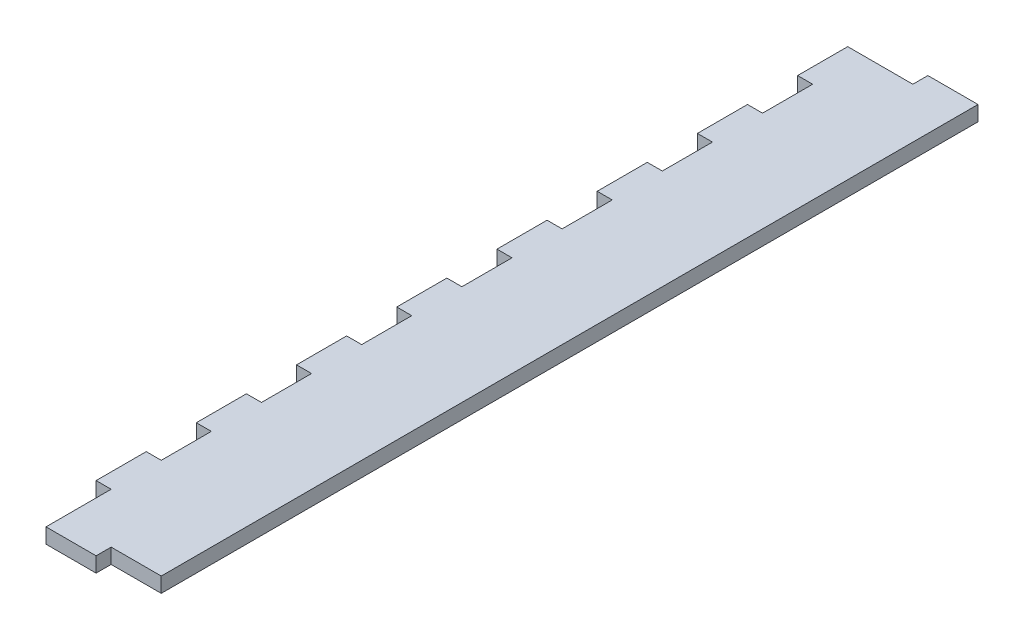
SolidWorks part; units mm, degrees
ref_plane "Front Plane" through (0, 0, 0) normal (0, 0, 1) x (1, 0, 0)
ref_plane "Top Plane" through (0, 0, 0) normal (0, 1, 0) x (1, 0, 0)
ref_plane "Right Plane" through (0, 0, 0) normal (1, 0, 0) x (0, 0, -1)
sketch "Sketch1" plane through (0, 0, 0) normal (0, 1, 0) x (1, 0, 0)
  line L0 (40, 80) -> (40, 70)
  line L1 (43, 70) -> (43, 60)
  line L2 (43, 60) -> (40, 60)
  line L3 (40, 70) -> (43, 70)
  line L4 (40, 60) -> (40, 50)
  line L5 (40, 50) -> (43, 50)
  line L6 (43, 50) -> (43, 40)
  line L7 (43, 40) -> (40, 40)
  line L8 (40, 40) -> (40, 30)
  line L9 (40, 30) -> (43, 30)
  line L10 (43, 30) -> (43, 20)
  line L11 (43, 20) -> (40, 20)
  line L12 (40, 20) -> (40, 10)
  line L13 (40, 10) -> (43, 10)
  line L14 (43, 10) -> (43, 0)
  line L15 (43, 0) -> (40, 0)
  line L16 (40, 0) -> (40, -10)
  line L17 (40, -10) -> (43, -10)
  line L18 (43, -10) -> (43, -20)
  line L19 (43, -20) -> (40, -20)
  line L20 (40, -20) -> (40, -30)
  line L21 (40, -30) -> (43, -30)
  line L22 (43, -30) -> (43, -40)
  line L23 (43, -40) -> (40, -40)
  line L24 (40, -40) -> (40, -50)
  line L25 (40, -50) -> (43, -50)
  line L26 (43, -50) -> (43, -60)
  line L27 (43, -60) -> (40, -60)
  line L28 (40, -60) -> (40, -70)
  line L29 (40, -70) -> (43, -70)
  line L30 (43, -70) -> (43, -80)
  line L31 (43, -80) -> (40, -80)
  line L32 (40, 80) -> (40, -80) construction
  line L33 (-956.5342, 0) -> (49043.4658, 0) construction
  line L34 (-40, -80) -> (-40, -70)
  line L35 (-43, -70) -> (-43, -60)
  line L36 (-43, -60) -> (-40, -60)
  line L37 (-40, -70) -> (-43, -70)
  line L38 (-40, -60) -> (-40, -50)
  line L39 (-40, -50) -> (-43, -50)
  line L40 (-43, -50) -> (-43, -40)
  line L41 (-43, -40) -> (-40, -40)
  line L42 (-40, -40) -> (-40, -30)
  line L43 (-40, -30) -> (-43, -30)
  line L44 (-43, -30) -> (-43, -20)
  line L45 (-43, -20) -> (-40, -20)
  line L46 (-40, -20) -> (-40, -10)
  line L47 (-40, -10) -> (-43, -10)
  line L48 (-43, -10) -> (-43, 0)
  line L49 (-43, 0) -> (-40, 0)
  line L50 (-40, 0) -> (-40, 10)
  line L51 (-40, 10) -> (-43, 10)
  line L52 (-43, 10) -> (-43, 20)
  line L53 (-43, 20) -> (-40, 20)
  line L54 (-40, 20) -> (-40, 30)
  line L55 (-40, 30) -> (-43, 30)
  line L56 (-43, 30) -> (-43, 40)
  line L57 (-43, 40) -> (-40, 40)
  line L58 (-40, 40) -> (-40, 50)
  line L59 (-40, 50) -> (-43, 50)
  line L60 (-43, 50) -> (-43, 60)
  line L61 (-43, 60) -> (-40, 60)
  line L62 (-40, 60) -> (-40, 70)
  line L63 (-40, 70) -> (-43, 70)
  line L64 (-43, 70) -> (-43, 80)
  line L65 (-43, 80) -> (-40, 80)
  line L66 (-40, -80) -> (-40, 80) construction
  line L67 (-40, 80) -> (-30, 80)
  line L68 (-30, 83) -> (-20, 83)
  line L69 (-20, 83) -> (-20, 80)
  line L70 (-30, 80) -> (-30, 83)
  line L71 (-20, 80) -> (-10, 80)
  line L72 (-40, 80) -> (40, 80) construction
  line L73 (-10, 80) -> (-10, 83)
  line L74 (-10, 83) -> (0, 83)
  line L75 (0, 83) -> (0, 80)
  line L76 (0, 80) -> (10, 80)
  line L77 (10, 80) -> (10, 83)
  line L78 (10, 83) -> (20, 83)
  line L79 (20, 83) -> (20, 80)
  line L80 (20, 80) -> (30, 80)
  line L81 (30, 80) -> (30, 83)
  line L82 (30, 83) -> (40, 83)
  line L83 (40, 83) -> (40, 80)
  line L84 (30, -83) -> (20, -83)
  line L85 (20, -83) -> (20, -80)
  line L86 (30, -80) -> (30, -83)
  line L87 (20, -80) -> (10, -80)
  line L88 (10, -80) -> (10, -83)
  line L89 (10, -83) -> (0, -83)
  line L90 (0, -83) -> (0, -80)
  line L91 (0, -80) -> (-10, -80)
  line L92 (-10, -80) -> (-10, -83)
  line L93 (-10, -83) -> (-20, -83)
  line L94 (-20, -83) -> (-20, -80)
  line L95 (-20, -80) -> (-30, -80)
  line L96 (-30, -80) -> (-30, -83)
  line L97 (-30, -83) -> (-40, -83)
  line L98 (-40, -83) -> (-40, -80)
  line L99 (40, -80) -> (30, -80)
  line L133 (0, -919.7936) -> (0, 49080.2064) construction
  line L134 (40, 80) -> (40, 70) [skipped]
  line L135 (43, 70) -> (43, 60) [skipped]
  line L136 (43, 60) -> (40, 60) [skipped]
  line L137 (40, 70) -> (43, 70) [skipped]
  line L138 (40, 60) -> (40, 50) [skipped]
  line L139 (40, 50) -> (43, 50) [skipped]
  line L140 (43, 50) -> (43, 40) [skipped]
  line L141 (43, 40) -> (40, 40) [skipped]
  line L142 (40, 40) -> (40, 30) [skipped]
  line L143 (40, 30) -> (43, 30) [skipped]
  line L144 (43, 30) -> (43, 20) [skipped]
  line L145 (43, 20) -> (40, 20) [skipped]
  line L146 (40, 20) -> (40, 10) [skipped]
  line L147 (40, 10) -> (43, 10) [skipped]
  line L148 (43, 10) -> (43, 0) [skipped]
  line L149 (43, 0) -> (40, 0) [skipped]
  line L150 (40, 0) -> (40, -10) [skipped]
  line L151 (40, -10) -> (43, -10) [skipped]
  line L152 (43, -10) -> (43, -20) [skipped]
  line L153 (43, -20) -> (40, -20) [skipped]
  line L154 (40, -20) -> (40, -30) [skipped]
  line L155 (40, -30) -> (43, -30) [skipped]
  line L156 (43, -30) -> (43, -40) [skipped]
  line L157 (43, -40) -> (40, -40) [skipped]
  line L158 (40, -40) -> (40, -50) [skipped]
  line L159 (40, -50) -> (43, -50) [skipped]
  line L160 (43, -50) -> (43, -60) [skipped]
  line L161 (43, -60) -> (40, -60) [skipped]
  line L162 (40, -60) -> (40, -70) [skipped]
  line L163 (40, -70) -> (43, -70) [skipped]
  line L164 (43, -70) -> (43, -80) [skipped]
  line L165 (43, -80) -> (40, -80) [skipped]
  line L166 (40, 80) -> (40, -80) construction
  line L167 (-40, -80) -> (-40, -70) [skipped]
  line L168 (-43, -70) -> (-43, -60) [skipped]
  line L169 (-43, -60) -> (-40, -60) [skipped]
  line L170 (-40, -70) -> (-43, -70) [skipped]
  line L171 (-40, -60) -> (-40, -50) [skipped]
  line L172 (-40, -50) -> (-43, -50) [skipped]
  line L173 (-43, -50) -> (-43, -40) [skipped]
  line L174 (-43, -40) -> (-40, -40) [skipped]
  line L175 (-40, -40) -> (-40, -30) [skipped]
  line L176 (-40, -30) -> (-43, -30) [skipped]
  line L177 (-43, -30) -> (-43, -20) [skipped]
  line L178 (-43, -20) -> (-40, -20) [skipped]
  line L179 (-40, -20) -> (-40, -10) [skipped]
  line L180 (-40, -10) -> (-43, -10) [skipped]
  line L181 (-43, -10) -> (-43, 0) [skipped]
  line L182 (-43, 0) -> (-40, 0) [skipped]
  line L183 (-40, 0) -> (-40, 10) [skipped]
  line L184 (-40, 10) -> (-43, 10) [skipped]
  line L185 (-43, 10) -> (-43, 20) [skipped]
  line L186 (-43, 20) -> (-40, 20) [skipped]
  line L187 (-40, 20) -> (-40, 30) [skipped]
  line L188 (-40, 30) -> (-43, 30) [skipped]
  line L189 (-43, 30) -> (-43, 40) [skipped]
  line L190 (-43, 40) -> (-40, 40) [skipped]
  line L191 (-40, 40) -> (-40, 50) [skipped]
  line L192 (-40, 50) -> (-43, 50) [skipped]
  line L193 (-43, 50) -> (-43, 60) [skipped]
  line L194 (-43, 60) -> (-40, 60) [skipped]
  line L195 (-40, 60) -> (-40, 70) [skipped]
  line L196 (-40, 70) -> (-43, 70) [skipped]
  line L197 (-43, 70) -> (-43, 80) [skipped]
  line L198 (-43, 80) -> (-40, 80) [skipped]
  line L199 (-40, -80) -> (-40, 80) construction
  point P74 (0, 80)
  point P88 (0, -80)
  dimension "D1" = 3
  dimension "D2" = 10
  dimension "D3" = 8
  dimension "D5" = 4
  dimension "D4" = 2
extrude "Boss-Extrude1" add sketch "Sketch1" along normal blind 3
sketch "Sketch2" plane through (0, 3, 0) normal (0, 1, 0) x (1, 0, 0)
  line L0 (-940.9488, 89.3893) -> (49059.0512, 89.3893) construction
  line L1 (-20, 89.3893) -> (59.0512, 89.3893)
  line L2 (-20, 89.3893) -> (-20, -92.2975)
  line L3 (-20, -92.2975) -> (59.0512, -92.2975)
  line L4 (59.0512, 89.3893) -> (59.0512, -92.2975)
  line L5 (-940.9488, -92.2975) -> (49059.0512, -92.2975) construction
extrude "Cut-Extrude1" cut sketch "Sketch2" against normal through all
